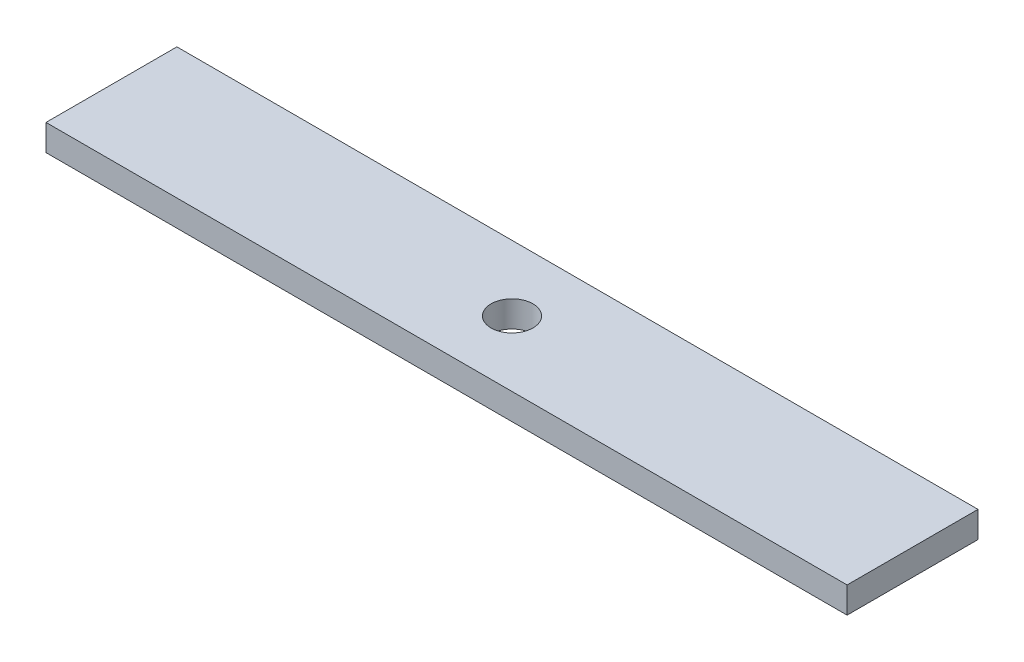
SolidWorks part; units mm, degrees
ref_plane "Front Plane" through (0, 0, 0) normal (0, 0, 1) x (1, 0, 0)
ref_plane "Top Plane" through (0, 0, 0) normal (0, 1, 0) x (1, 0, 0)
ref_plane "Right Plane" through (0, 0, 0) normal (1, 0, 0) x (0, 0, -1)
sketch "Sketch1" plane through (0, 0, 0) normal (0, 1, 0) x (1, 0, 0)
  line L1 (-76.5, 0) -> (76.5, 0)
  line L2 (-76.5, 0) -> (-76.5, 25)
  line L3 (-76.5, 25) -> (76.5, 25)
  line L4 (76.5, 0) -> (76.5, 25)
  line L5 (-76.5, 0) -> (76.5, 25) construction
  line L6 (-76.5, 25) -> (76.5, 0) construction
  circle A1 centre (0, 12.5) radius 4
  point P7 (0, 0)
  point P8 (0, 0)
  dimension "D3" = 8
  dimension "D1" = 153
  dimension "D2" = 25
  dimension "D4" = 12.5
extrude "Boss-Extrude1" add sketch "Sketch1" along normal blind 5
